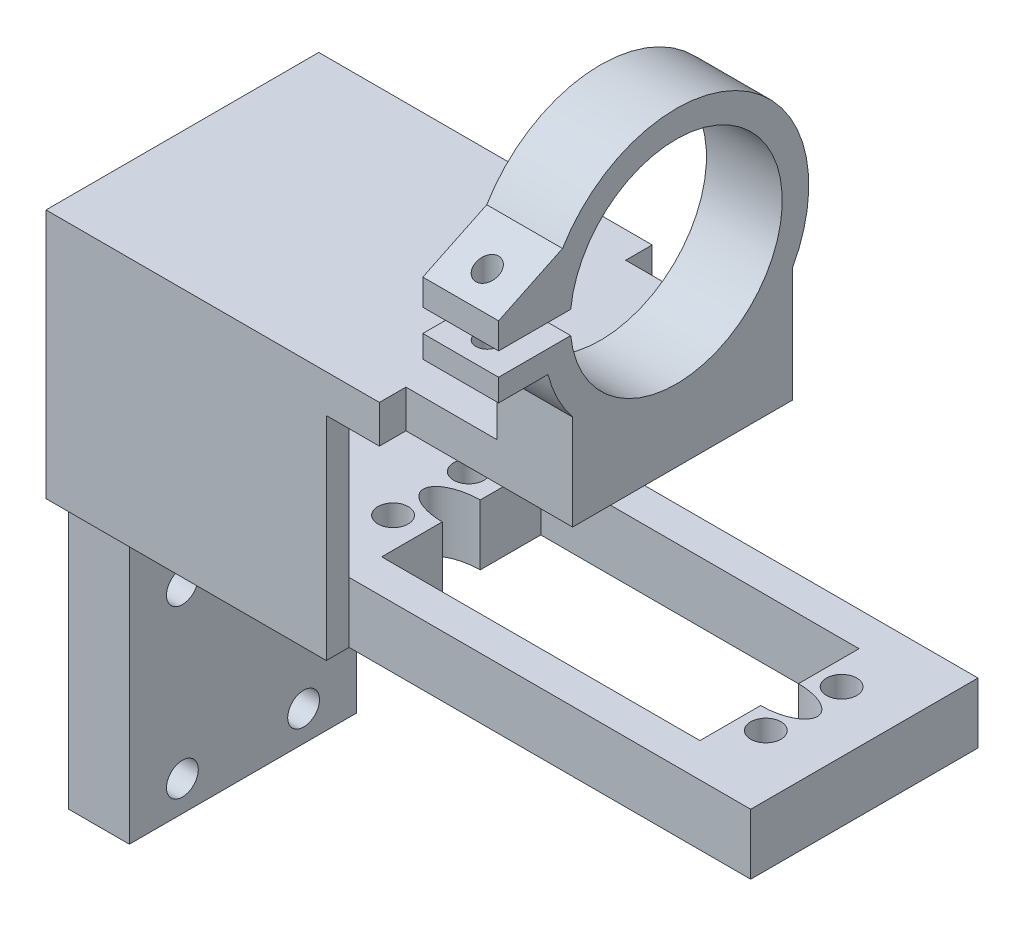
SolidWorks part; units mm, degrees
material "ABS"
ref_plane "前基準面" through (0, 0, 0) normal (0, 0, 1) x (1, 0, 0)
ref_plane "上基準面" through (0, 0, 0) normal (0, 1, 0) x (1, 0, 0)
ref_plane "右基準面" through (0, 0, 0) normal (1, 0, 0) x (0, 0, -1)
sketch "草圖1" plane through (0, 0, 0) normal (0, 1, 0) x (1, 0, 0)
  line L1 (0, 0) -> (82, 0)
  line L2 (0, 0) -> (0, 30)
  line L3 (0, 30) -> (82, 30)
  line L4 (82, 0) -> (82, 30)
  dimension "D1" = 82
  dimension "D2" = 30
extrude "填料-伸長1" add sketch "草圖1" along normal blind 8
sketch "草圖2" plane through (0, 8, 0) normal (0, 1, 0) x (1, 0, 0)
  line L1 (28.8, 25.5) -> (70.8, 25.5)
  line L3 (28.8, 4.5) -> (70.8, 4.5)
  line L6 (82, 30) -> (0, 30) construction
  line L7 (28.8, 25.5) -> (28.8, 17.5)
  line L8 (70.8, 25.5) -> (70.8, 17.5)
  line L9 (70.8, 12.5) -> (70.8, 4.5)
  line L10 (28.8, 12.5) -> (28.8, 4.5)
  line L11 (0, 30) -> (0, 0) construction
  line L12 (82, 0) -> (82, 30) construction
  circle A0 centre (74, 20) radius 2
  circle A1 centre (74, 10) radius 2
  circle A2 centre (24.8, 20) radius 2
  circle A3 centre (24.8, 10) radius 2
  ellipse E0 centre (70.8, 15) end of major axis (75.8, 15) minor radius 2.5 (70.8, 12.5) -> (70.8, 17.5) ccw
  ellipse E1 centre (28.8, 15) end of major axis (33.8, 15) minor radius 2.5 (28.8, 17.5) -> (28.8, 12.5) ccw
  dimension "D4" = 10
  dimension "D1" = 21
  dimension "D2" = 42
  dimension "D3" = 4.5
  dimension "D5" = 10
  dimension "D6" = 10
  dimension "D7" = 10
  dimension "D8" = 5
  dimension "D9" = 5
  dimension "D10" = 10
  dimension "D11" = 8
  dimension "D12" = 10
  dimension "D13" = 8
  dimension "24.8" = 24.8
  dimension "D15" = 8
  dimension "D16" = 28.8
extrude "除料-伸長1" cut sketch "草圖2" against normal blind 8
sketch "草圖4" plane through (0, 8, 0) normal (0, 1, 0) x (1, 0, 0)
  line L0 (0, 30) -> (0, 0)
  line L9 (0, 0) -> (-8, 0)
  line L10 (-8, 0) -> (-8, 30)
  line L11 (-8, 30) -> (0, 30)
  dimension "D1" = 8
extrude "填料-伸長2" add sketch "草圖4" against normal blind 45
sketch "草圖14" plane through (0, 0, 0) normal (0, 0, 1) x (1, 0, 0)
  line L0 (0, 0) -> (0, -2)
  line L1 (0, -37) -> (0, 0) construction
  line L2 (0, -2) -> (2, 0)
  line L3 (0, 0) -> (82, 0) construction
  line L4 (2, 0) -> (0, 0)
  dimension "D1" = 2
  dimension "D2" = 2
extrude "填料-伸長5" add sketch "草圖14" against normal blind 30
sketch "草圖15" plane through (0, 0, 0) normal (1, 0, 0) x (0, 0, -1)
  line L0 (0, -37) -> (30, -37) construction
  line L1 (0, -37) -> (0, -2) construction
  circle A0 centre (7, -33) radius 2.1
  circle A5 centre (7, -11) radius 2.1
  circle A13 centre (23, -11) radius 2.1
  circle A16 centre (23, -33) radius 2.1
  circle A19 centre (15, -11) radius 2.1 [skipped]
  circle A20 centre (15, -33) radius 2.1 [skipped]
  dimension "D1" = 4
  dimension "D2" = 22
  dimension "D3" = 4.2
  dimension "D4" = 4.2
  dimension "D6" = 7
  dimension "D7" = 3
extrude "除料-伸長2" cut sketch "草圖15" against normal blind 10
sketch "草圖17" plane through (0, 8, 0) normal (0, 1, 0) x (1, 0, 0)
  line L1 (-8, 0) -> (29, 0)
  line L2 (-8, 0) -> (-8, -3)
  line L3 (-8, -3) -> (29, -3)
  line L4 (29, 0) -> (29, -3)
  line L5 (-8, 30) -> (29, 30)
  line L6 (-8, 30) -> (-8, 33)
  line L7 (-8, 33) -> (29, 33)
  line L8 (29, 30) -> (29, 33)
  dimension "D1" = 37
  dimension "D2" = 37
  dimension "D3" = 3
  dimension "D4" = 3
extrude "填料-伸長6" add sketch "草圖17" along normal blind 20 separate body
sketch "草圖18" plane through (0, 28, 0) normal (0, 1, 0) x (1, 0, 0)
  line L0 (-8, 33) -> (58, 33)
  line L1 (58, 33) -> (58, -3)
  line L2 (58, -3) -> (-8, -3)
  line L3 (-8, -3) -> (-8, 33)
  dimension "D1" = 66
extrude "填料-伸長7" add sketch "草圖18" along normal blind 5
sketch "草圖19" plane through (0, 8, 0) normal (0, -1, 0) x (-1, 0, 0)
  line L1 (-29, -3) -> (8, -3)
  line L2 (-29, -3) -> (-29, 0)
  line L3 (-29, 0) -> (8, 0)
  line L4 (8, -3) -> (8, 0)
  line L5 (8, 33) -> (-29, 33)
  line L6 (8, 33) -> (8, 30)
  line L7 (8, 30) -> (-29, 30)
  line L8 (-29, 33) -> (-29, 30)
extrude "填料-伸長8" add sketch "草圖19" along normal up to vertex
sketch "草圖20" plane through (0, 33, 0) normal (0, 1, 0) x (1, 0, 0)
  line L0 (58, -3) -> (58, 33) construction
  line L1 (58, 33) -> (36, 33)
  line L2 (58, 33) -> (58, 29.5)
  line L3 (58, 29.5) -> (36, 29.5)
  line L4 (36, 33) -> (36, 29.5)
  line L5 (58, -3) -> (36, -3)
  line L6 (58, -3) -> (58, 0.5)
  line L7 (58, 0.5) -> (36, 0.5)
  line L8 (36, -3) -> (36, 0.5)
  dimension "D1" = 29
  dimension "D2" = 3.5
  dimension "D3" = 22
  dimension "D4" = 22
extrude "除料-伸長3" cut sketch "草圖20" against normal up to vertex (5 mm away)
sketch "草圖21" plane through (58, 0, 0) normal (1, 0, 0) x (0, 0, -1)
  line L1 (0.5, 28) -> (29.5, 28) construction
  circle A0 centre (14.1668, 51.5) radius 14
  circle A1 centre (14.1668, 51.5) radius 17.5
  dimension "D1" = 28
  dimension "D2" = 35
  dimension "D3" = 23.5
extrude "填料-伸長9" add sketch "草圖21" against normal blind 10 separate body
sketch "草圖22" plane through (58, 0, 0) normal (1, 0, 0) x (0, 0, -1)
  line L1 (2.1514, 50.0145) -> (-5.66, 50.0145)
  line L2 (2.1514, 50.0145) -> (2.1514, 53.0145)
  line L3 (2.1514, 53.0145) -> (-5.66, 53.0145)
  line L4 (-5.66, 50.0145) -> (-5.66, 53.0145)
  dimension "3" = 3
extrude "除料-伸長4" cut sketch "草圖22" against normal blind 10
sketch "草圖23" plane through (58, 0, 0) normal (1, 0, 0) x (0, 0, -1)
  line L0 (-3.2676, 53.0145) -> (-9.2676, 53.0145)
  line L1 (-9.2676, 53.0145) -> (-9.2676, 56.4579)
  line L2 (-9.2676, 56.4579) -> (-0.8354, 60.5104)
  line L3 (-0.8354, 60.5104) -> (-3.2676, 53.0145)
  line L4 (-3.2701, 50.0145) -> (-9.2701, 50.0145)
  line L5 (-9.2701, 50.0145) -> (-9.2701, 47.0726)
  line L6 (-9.2701, 47.0726) -> (-2.7639, 47.0726)
  line L7 (-2.7639, 47.0726) -> (-3.2701, 50.0145)
  line L8 (0.5, 33) -> (0.5, 40.5698)
  line L9 (0.5, 40.5698) -> (14.1668, 34)
  line L10 (14.1668, 34) -> (25.3775, 38.0624)
  line L12 (29.5, 33) -> (29.5, 43.0654)
  line L13 (29.5, 43.0654) -> (25.3775, 38.0624)
  line L14 (0.5, 33) -> (29.5, 33)
  arc A0 (-3.2701, 50.0145) -> (-3.2676, 53.0145) centre (14.1668, 51.5) ccw construction
  dimension "D1" = 6
  dimension "D2" = 6
extrude "填料-伸長10" add sketch "草圖23" against normal blind 10
sketch "草圖24" plane through (0, 47.0726, 0) normal (0, -1, 0) x (-1, 0, 0)
  line L0 (-58, -9.2701) -> (-58, -2.7639) construction
  line L1 (-48, -2.7639) -> (-58, -2.7639) construction
  circle A0 centre (-53, -5.7639) radius 1.5
  dimension "D1" = 3
  dimension "D2" = 5
  dimension "D3" = 3
extrude "除料-伸長5" cut sketch "草圖24" against normal blind 13
